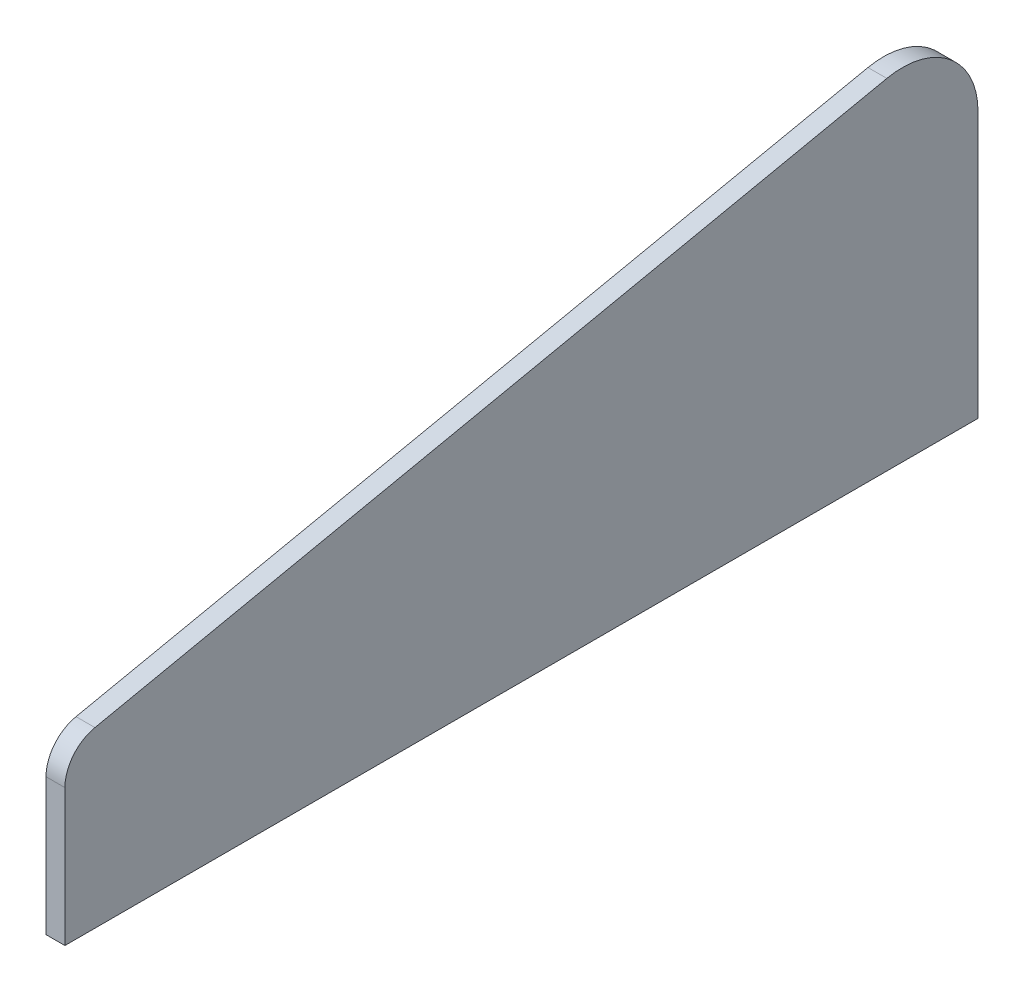
SolidWorks part; units mm, degrees
ref_plane "Front Plane" through (0, 0, 0) normal (0, 0, 1) x (1, 0, 0)
ref_plane "Top Plane" through (0, 0, 0) normal (0, 1, 0) x (1, 0, 0)
ref_plane "Right Plane" through (0, 0, 0) normal (1, 0, 0) x (0, 0, -1)
sketch "Sketch1" plane through (0, 0, 0) normal (1, 0, 0) x (0, 0, -1)
  line L2 (44.2102, 18.6733) -> (552.2102, 18.6733)
  line L3 (552.2102, 18.6733) -> (552.2102, 259.9733)
  line L4 (-61.2777, 131.1986) -> (552.2102, 259.9733)
  line L6 (-61.2777, 18.6733) -> (44.2102, 18.6733)
  line L7 (-61.2777, 131.1986) -> (-61.2777, 18.6733)
  dimension "D1" = 241.3
extrude "Boss-Extrude1" add sketch "Sketch1" along normal blind 12.7 contours L6 L2 L3 L4 L7
fillet "Fillet2" radius 50.8 1 edges at (6.35, 259.9733, -552.2102)
fillet "Fillet3" radius 25.4 1 edges at (6.35, 131.1986, 61.2777)
sketch "Sketch2" plane through (0, -2.3511, -40.6581) normal (-1, 0, 0) x (0, -0.0523, 0.9986)
  line L3 (-93.7223, 66.1733) -> (-73.7223, 66.1733)
  line L4 (-93.7223, 66.1733) -> (-93.7223, 71.1733)
  line L5 (-93.7223, 71.1733) -> (-73.7223, 71.1733)
  line L6 (-73.7223, 66.1733) -> (-73.7223, 71.1733)
  line L7 (-93.7223, 66.1733) -> (-73.7223, 71.1733) construction
  line L8 (-93.7223, 71.1733) -> (-73.7223, 66.1733) construction
  point P0 (-83.7223, 68.6733)
  point P5 (-83.7223, 68.6733)
  dimension "D3" = 20
  dimension "D4" = 5
extrude "Cut-Extrude1" cut sketch "Sketch2" against normal blind 5
sketch "Sketch3" plane through (0, -30.5161, -7.8267) normal (-1, 0, 0) x (0, -0.1045, 0.9945)
  line L3 (-340.717, 106.6163) -> (-320.717, 106.6163)
  line L4 (-340.717, 106.6163) -> (-340.717, 111.6163)
  line L5 (-340.717, 111.6163) -> (-320.717, 111.6163)
  line L6 (-320.717, 106.6163) -> (-320.717, 111.6163)
  line L7 (-340.717, 106.6163) -> (-320.717, 111.6163) construction
  line L8 (-340.717, 111.6163) -> (-320.717, 106.6163) construction
  point P0 (-330.717, 109.1163)
  point P1 (-330.717, 109.1163)
  dimension "D1" = 20
  dimension "D2" = 5
extrude "Cut-Extrude2" cut sketch "Sketch3" against normal blind 5
